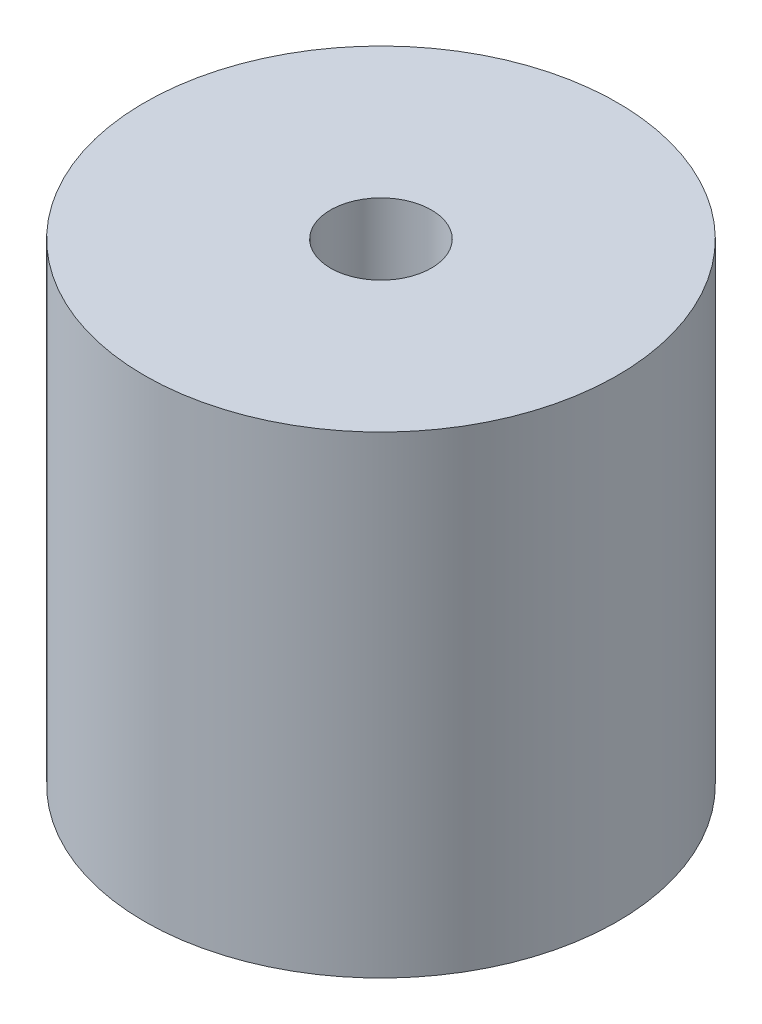
SolidWorks part; units mm, degrees
ref_plane "Front Plane" through (0, 0, 0) normal (0, 0, 1) x (1, 0, 0)
ref_plane "Top Plane" through (0, 0, 0) normal (0, 1, 0) x (1, 0, 0)
ref_plane "Right Plane" through (0, 0, 0) normal (1, 0, 0) x (0, 0, -1)
sketch "Sketch1" plane through (0, 0, 0) normal (0, 1, 0) x (1, 0, 0)
  circle A0 centre (0, 0) radius 7.5
  circle A1 centre (0, 0) radius 1.6
  dimension "D1" = 15
  dimension "D2" = 3.2
extrude "Boss-Extrude1" add sketch "Sketch1" along normal blind 15
